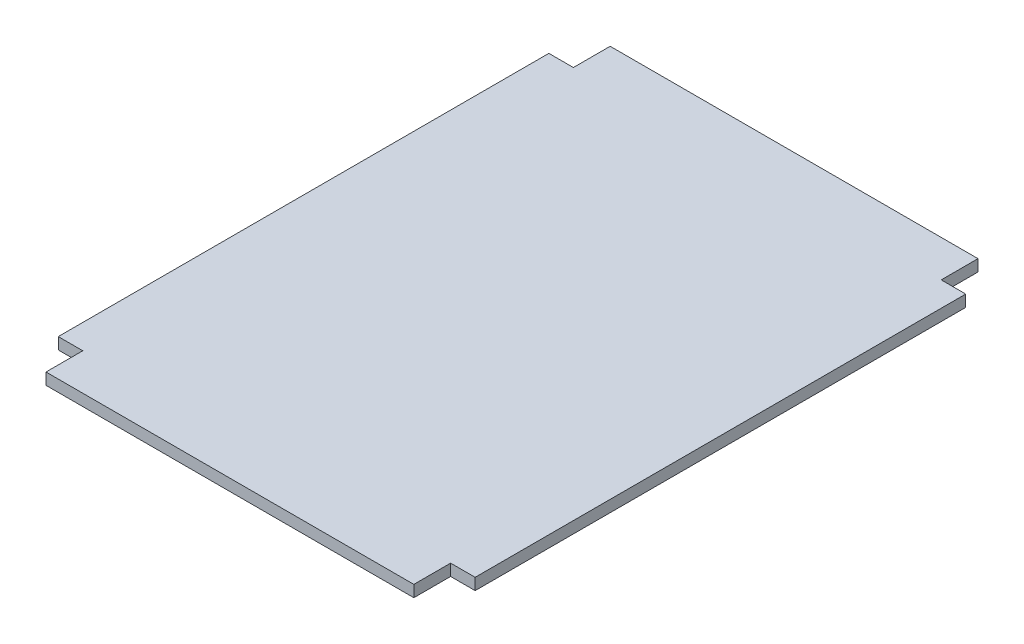
SolidWorks part; units mm, degrees
ref_plane "Front Plane" through (0, 0, 0) normal (0, 0, 1) x (1, 0, 0)
ref_plane "Top Plane" through (0, 0, 0) normal (0, 1, 0) x (1, 0, 0)
ref_plane "Right Plane" through (0, 0, 0) normal (1, 0, 0) x (0, 0, -1)
sketch "Sketch1" plane through (0, 0, 0) normal (0, 1, 0) x (1, 0, 0)
  line L0 (-53.9623, 66.4972) -> (53.9623, 66.4972) construction
  line L1 (53.9623, -73.025) -> (-53.9623, -73.025)
  line L2 (53.9623, -73.025) -> (53.9623, 73.025)
  line L3 (53.9623, 73.025) -> (-53.9623, 73.025)
  line L4 (-53.9623, -73.025) -> (-53.9623, 73.025)
  line L5 (53.9623, -73.025) -> (-53.9623, 73.025) construction
  line L6 (53.9623, 73.025) -> (-53.9623, -73.025) construction
  line L7 (-53.9623, -66.4972) -> (53.9623, -66.4972) construction
  line L8 (-53.9623, 66.4972) -> (-53.9623, -66.4972) construction
  line L9 (53.9623, 66.4972) -> (53.9623, -66.4972) construction
  line L20 (-53.9623, -73.025) -> (-47.6123, -73.025)
  line L29 (-53.9623, -73.025) -> (-53.9623, -63.5)
  line L34 (-53.9623, -63.5) -> (-47.6123, -63.5)
  line L39 (-47.6123, -73.025) -> (-47.6123, -63.5)
  line L40 (53.9623, -73.025) -> (47.6123, -73.025)
  line L41 (53.9623, -73.025) -> (53.9623, -63.5)
  line L42 (53.9623, -63.5) -> (47.6123, -63.5)
  line L43 (47.6123, -73.025) -> (47.6123, -63.5)
  line L44 (53.9623, 73.025) -> (47.6123, 73.025)
  line L45 (53.9623, 73.025) -> (53.9623, 63.5)
  line L46 (53.9623, 63.5) -> (47.6123, 63.5)
  line L47 (47.6123, 73.025) -> (47.6123, 63.5)
  line L48 (-53.9623, 73.025) -> (-47.6123, 73.025)
  line L49 (-53.9623, 73.025) -> (-53.9623, 63.5)
  line L50 (-53.9623, 63.5) -> (-47.6123, 63.5)
  line L51 (-47.6123, 73.025) -> (-47.6123, 63.5)
  point P0 (0, 0)
  point P10 (53.9623, 0)
  point P11 (53.9623, 0)
  point P24 (0, 0)
  dimension "D1" = 107.9246
  dimension "D2" = 146.05
  dimension "D3" = 132.9944
  dimension "D4" = 6.35
  dimension "D5" = 127
extrude "Boss-Extrude1" add sketch "Sketch1" along normal blind 2.9972
